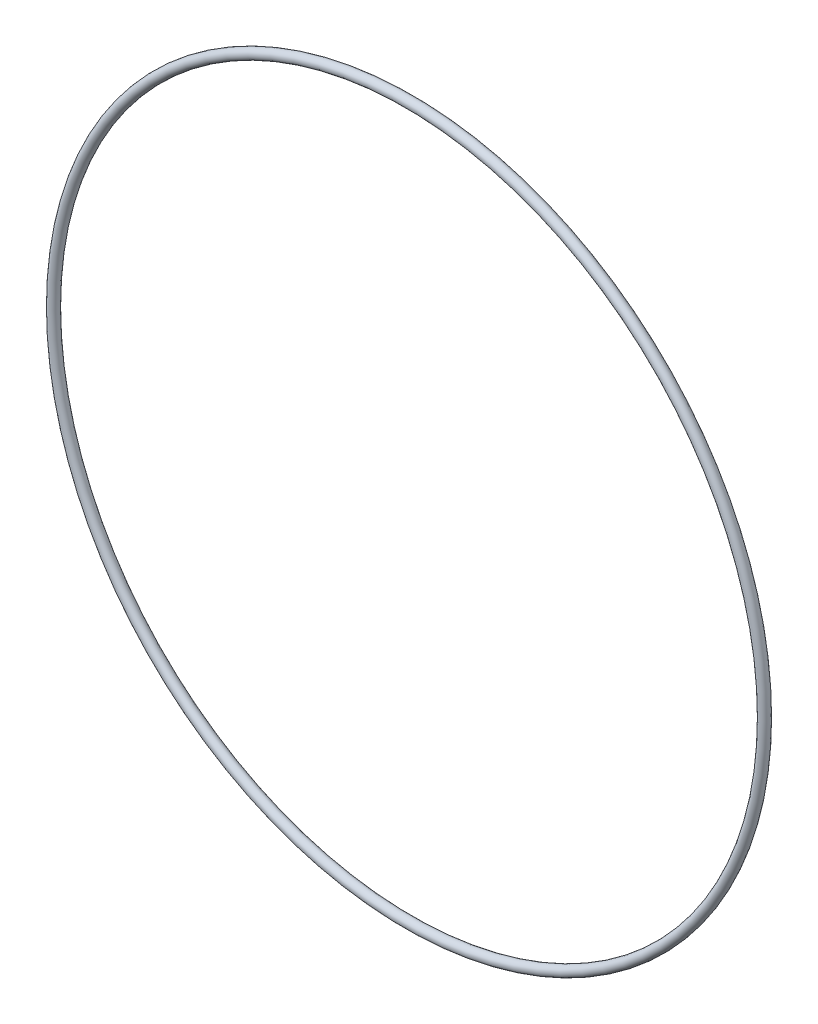
SolidWorks part; units mm, degrees
material "O-Ring (NBR)"
ref_plane "Front Plane" through (0, 0, 0) normal (0, 0, 1) x (1, 0, 0)
ref_plane "Top Plane" through (0, 0, 0) normal (0, 1, 0) x (1, 0, 0)
ref_plane "Right Plane" through (0, 0, 0) normal (1, 0, 0) x (0, 0, -1)
sketch "Sketch7" plane through (0, 0, 0) normal (1, 0, 0) x (0, 0, -1)
  line L0 (0, 0) -> (93.9569, 0) construction
  circle A0 centre (0, 106.25) radius 1.5
  dimension "D1" = 3
  dimension "D2" = 209.5
revolve "Revolve1" add sketch "Sketch7" angle 360 about L0
sketch "Sketch6" plane through (0, 0, 0) normal (0, 1, 0) x (1, 0, 0)
  circle A0 centre (97.95, 0) radius 1.5
  dimension "D1" = 3
sketch "Sketch5" plane through (0, 0, 0) normal (0, 0, 1) x (1, 0, 0)
  line L1 (-81.95, -78.9) -> (81.95, -78.9)
  line L2 (-97.95, -62.9) -> (-97.95, 62.9)
  line L3 (-81.95, 78.9) -> (81.95, 78.9)
  line L4 (97.95, -62.9) -> (97.95, 62.9)
  line L5 (-97.95, -78.9) -> (97.95, 78.9) construction
  line L6 (-97.95, 78.9) -> (97.95, -78.9) construction
  arc A0 (-97.95, -62.9) -> (-81.95, -78.9) centre (-81.95, -62.9) ccw
  arc A1 (81.95, -78.9) -> (97.95, -62.9) centre (81.95, -62.9) ccw
  arc A2 (97.95, 62.9) -> (81.95, 78.9) centre (81.95, 62.9) ccw
  arc A3 (-81.95, 78.9) -> (-97.95, 62.9) centre (-81.95, 62.9) ccw
  point P0 (0, 0)
  dimension "D3" = 16
  dimension "D1" = 195.9
  dimension "D2" = 157.8
sweep "Sweep3" [suppressed] add profiles "Sketch6" path "Sketch5"
sketch "Sketch8" [suppressed] plane through (0, 0, 0) normal (0, 0, 1) x (1, 0, 0)
  line L0 (0, 0) -> (0, 113.7747) construction
  line L1 (-69.1, 74.5) -> (69.1, 74.5) construction
  line L2 (-91.1, 52.5) -> (-91.1, -60.5) construction
  line L3 (-70.1, -81.5) -> (-33, -81.5) construction
  line L4 (91.1, 52.5) -> (91.1, -60.5) construction
  line L5 (-33, -81.5) -> (-25, -90.5) construction
  line L6 (-25, -90.5) -> (25, -90.5) construction
  line L7 (25, -90.5) -> (33, -81.5) construction
  line L8 (33, -81.5) -> (70.1, -81.5) construction
  line L9 (-32.1081, -85.5138) -> (-27.6882, -90.4862)
  line L10 (-23.2037, -92.5) -> (23.2037, -92.5)
  line L11 (27.6882, -90.4862) -> (32.1081, -85.5138)
  line L12 (36.5925, -83.5) -> (70.1, -83.5)
  line L13 (93.1, 52.5) -> (93.1, -60.5)
  line L14 (-69.1, 76.5) -> (69.1, 76.5)
  line L15 (-93.1, 52.5) -> (-93.1, -60.5)
  line L16 (-70.1, -83.5) -> (-36.5925, -83.5)
  line L17 (-33.8981, -83.5) -> (-25.8981, -92.5) construction
  line L18 (-70.1, -83.5) -> (-33.8981, -83.5) construction
  line L19 (-25.8981, -92.5) -> (25.8981, -92.5) construction
  line L20 (25.8981, -92.5) -> (33.8981, -83.5) construction
  line L21 (33.8981, -83.5) -> (70.1, -83.5) construction
  arc A0 (91.1, 52.5) -> (69.1, 74.5) centre (69.1, 52.5) ccw construction
  arc A1 (-91.1, 52.5) -> (-69.1, 74.5) centre (-69.1, 52.5) cw construction
  arc A2 (-91.1, -60.5) -> (-70.1, -81.5) centre (-70.1, -60.5) ccw construction
  arc A3 (70.1, -81.5) -> (91.1, -60.5) centre (70.1, -60.5) ccw construction
  arc A4 (-32.1081, -85.5138) -> (-36.5925, -83.5) centre (-36.5925, -89.5) ccw
  arc A5 (70.1, -83.5) -> (93.1, -60.5) centre (70.1, -60.5) ccw
  arc A6 (93.1, 52.5) -> (69.1, 76.5) centre (69.1, 52.5) ccw
  arc A7 (-93.1, 52.5) -> (-69.1, 76.5) centre (-69.1, 52.5) cw
  arc A8 (-93.1, -60.5) -> (-70.1, -83.5) centre (-70.1, -60.5) ccw
  arc A9 (-27.6882, -90.4862) -> (-23.2037, -92.5) centre (-23.2037, -86.5) ccw
  arc A10 (23.2037, -92.5) -> (27.6882, -90.4862) centre (23.2037, -86.5) ccw
  arc A11 (32.1081, -85.5138) -> (36.5925, -83.5) centre (36.5925, -89.5) cw
  dimension "D2" = 22
  dimension "D4" = 22
  dimension "D5" = 156
  dimension "D6" = 21
  dimension "D11" = 6
  dimension "D1" = 182.2
  dimension "D3" = 74.5
  dimension "D7" = 66
  dimension "D8" = 50
  dimension "D9" = 165
  dimension "D10" = 2
sketch "Sketch9" [suppressed] plane through (0, 0, 0) normal (1, 0, 0) x (0, 0, -1)
  line L0 (0, 0) -> (0, 113.7747) construction
  circle A0 centre (0, 76.5) radius 1.5
  dimension "D1" = 3
sweep "Sweep5" [suppressed] add profiles "Sketch9" path "Sketch8"
